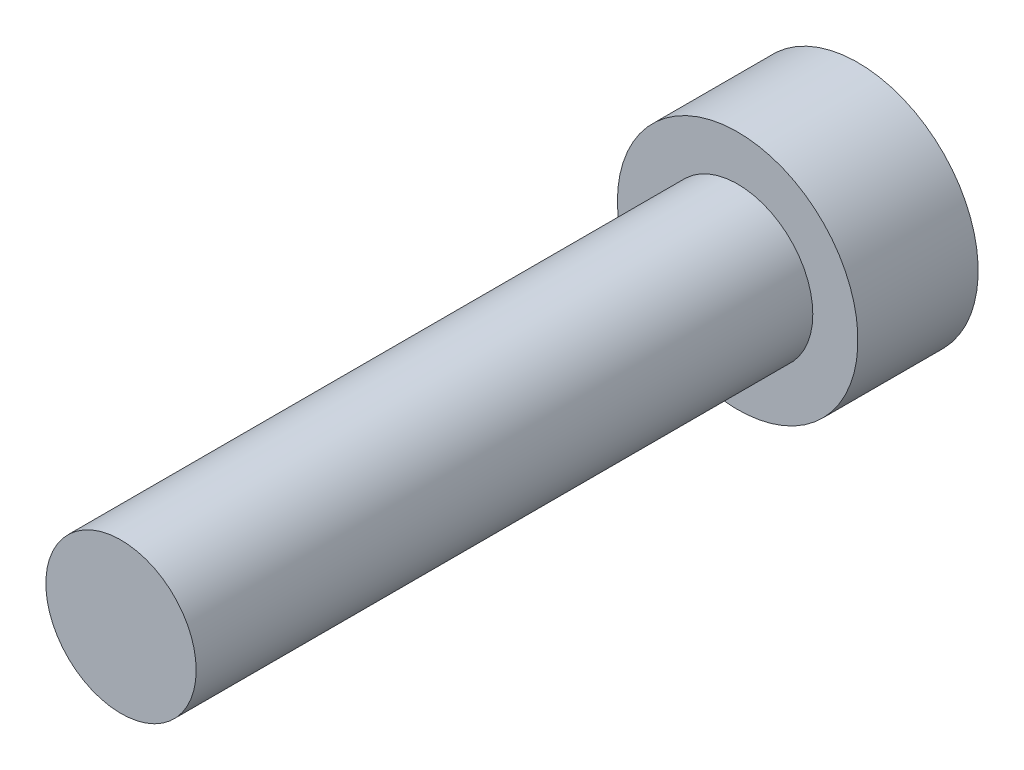
SolidWorks part; units mm, degrees
ref_plane "Front Plane" through (0, 0, 0) normal (0, 0, 1) x (1, 0, 0)
ref_plane "Top Plane" through (0, 0, 0) normal (0, 1, 0) x (1, 0, 0)
ref_plane "Right Plane" through (0, 0, 0) normal (1, 0, 0) x (0, 0, -1)
sketch "Sketch1" plane through (0, 0, 0) normal (0, 0, 1) x (1, 0, 0)
  circle A0 centre (0, 0) radius 4.9318
  circle A1 centre (0, 0) radius 2.5
  dimension "D1" = 5
extrude "Boss-Extrude1" add sketch "Sketch1" along normal blind 20.5104 contours A1
sketch "Sketch2" plane through (0, 0, 0) normal (0, 0, -1) x (-1, 0, 0)
  circle A0 centre (0, 0) radius 4
  dimension "D1" = 8
extrude "Boss-Extrude2" add sketch "Sketch2" along normal blind 4
sketch "Sketch3" plane through (0, 0, -4) normal (0, 0, -1) x (-1, 0, 0)
  line L1 (-0.5885, 3.3473) -> (-3.1931, 1.164)
  line L2 (-3.1931, 1.164) -> (-2.6046, -2.1833)
  line L3 (-2.6046, -2.1833) -> (0.5885, -3.3473)
  line L4 (0.5885, -3.3473) -> (3.1931, -1.164)
  line L5 (3.1931, -1.164) -> (2.6046, 2.1833)
  line L6 (2.6046, 2.1833) -> (-0.5885, 3.3473)
  circle A0 centre (0, 0) radius 2.9433 construction
extrude "Cut-Extrude1" cut sketch "Sketch3" against normal blind 2
